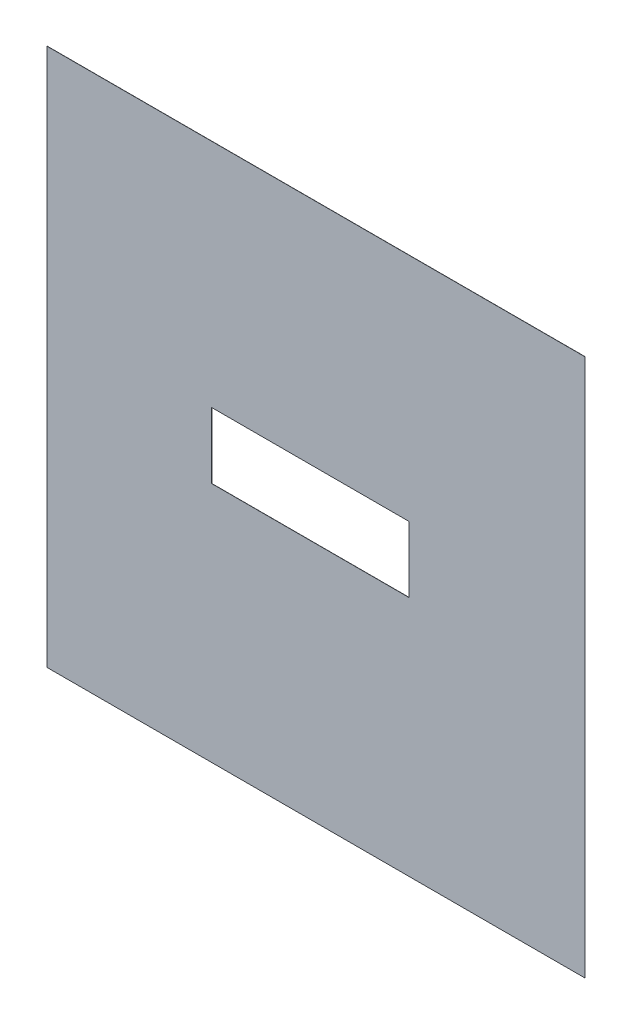
SolidWorks part; units mm, degrees
material "Copper"
ref_plane "Front Plane" through (0, 0, 0) normal (0, 0, 1) x (1, 0, 0)
ref_plane "Top Plane" through (0, 0, 0) normal (0, 1, 0) x (1, 0, 0)
ref_plane "Right Plane" through (0, 0, 0) normal (1, 0, 0) x (0, 0, -1)
sketch "Sketch1" plane through (0, 0, 0) normal (0, 0, 1) x (1, 0, 0)
  line L1 (0, 0) -> (98, 0)
  line L2 (0, 0) -> (0, -98)
  line L3 (0, -98) -> (98, -98)
  line L4 (98, 0) -> (98, -98)
  dimension "D1" = 98
  dimension "D2" = 98
extrude "Boss-Extrude1" add sketch "Sketch1" along normal blind 0.035
sketch "Sketch2" plane through (0, 0, 0) normal (0, 0, -1) x (-1, 0, 0)
  line L0 (-98, 0) -> (0, 0) construction
  line L1 (-66, -42) -> (-30, -42)
  line L2 (-66, -42) -> (-66, -54)
  line L3 (-66, -54) -> (-30, -54)
  line L4 (-30, -42) -> (-30, -54)
  line L5 (-98, -98) -> (-98, 0) construction
  dimension "D1" = 42
  dimension "D2" = 32
  dimension "D3" = 12
  dimension "D4" = 36
extrude "Cut-Extrude1" cut sketch "Sketch2" against normal blind 10
